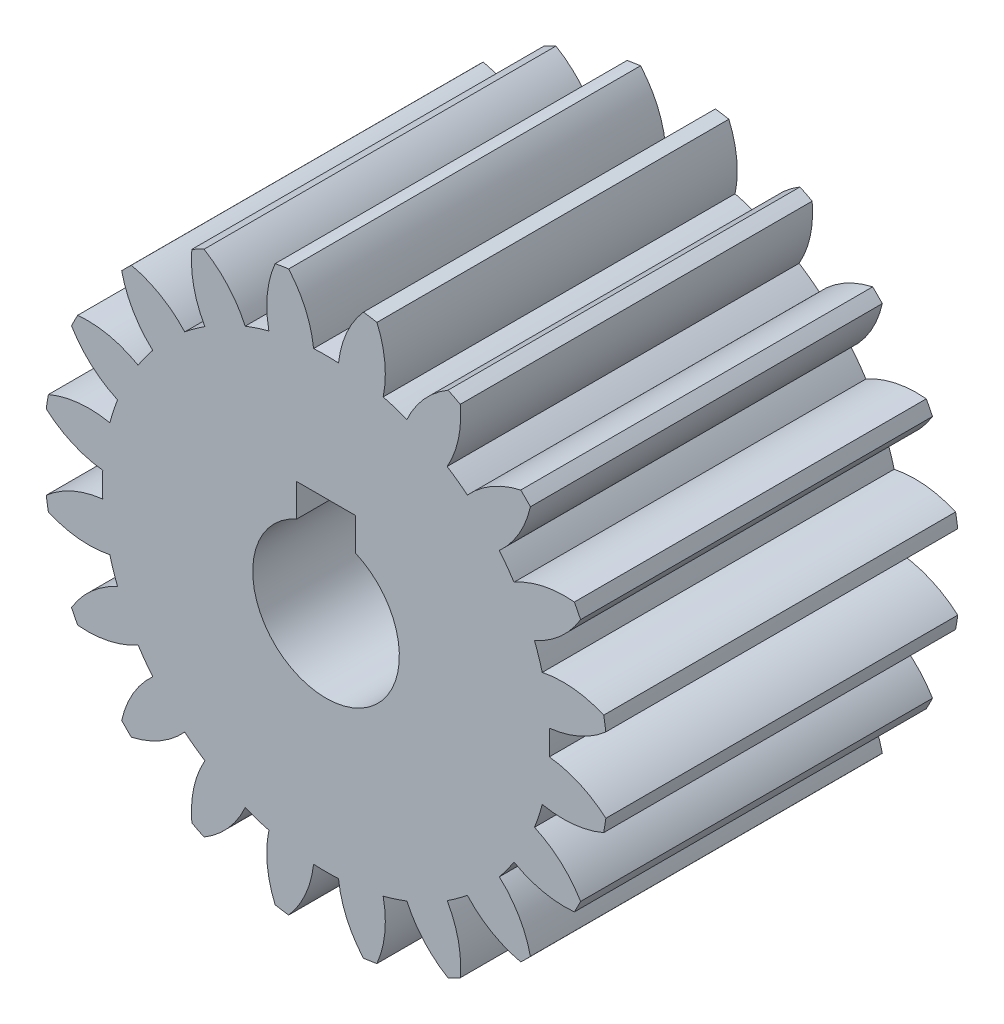
SolidWorks part; units mm, degrees
ref_plane "Front Plane" through (0, 0, 0) normal (0, 0, 1) x (1, 0, 0)
ref_plane "Top Plane" through (0, 0, 0) normal (0, 1, 0) x (1, 0, 0)
ref_plane "Right Plane" through (0, 0, 0) normal (1, 0, 0) x (0, 0, -1)
sketch "Sketch1" plane through (0, 0, 0) normal (0, 0, 1) x (1, 0, 0)
  circle A0 centre (0, 0) radius 19.25
  dimension "D1" = 38.5
extrude "Boss-Extrude1" add sketch "Sketch1" along normal mid plane 24
sketch "Sketch2" plane through (0, 0, 12) normal (0, 0, 1) x (1, 0, 0)
  line L0 (0, 0) -> (0, 17.5) construction
  circle A0 centre (0, 0) radius 17.5 construction
  arc A1 (0.85, 15.2263) -> (-0.85, 15.2263) centre (0, 0) ccw
  arc A2 (0.85, 15.2263) -> (2.55, 19.0804) centre (7.8078, 14.4592) cw
  circle A3 centre (0, 0) radius 19.25 construction
  arc A4 (-0.85, 15.2263) -> (-2.55, 19.0804) centre (-7.8078, 14.4592) ccw
  arc A5 (2.55, 19.0804) -> (-2.55, 19.0804) centre (0, 0) ccw
  point P12 (0, 13.7514)
  dimension "D1" = 35
  dimension "D2" = 30.5
  dimension "D5" = 7
  dimension "D3" = 1.7
  dimension "D4" = 5.1
extrude "Cut-Extrude1" cut sketch "Sketch2" against normal through all
pattern_circular "CirPattern1" count 20 over 360 about axis through (0, 0, 0) along (0, 0, 1) of "Cut-Extrude1"
sketch "Sketch3" plane through (0, 0, 12) normal (0, 0, 1) x (1, 0, 0)
  line L0 (2, 6.8) -> (2, 4.5826)
  line L1 (2, 6.8) -> (-2, 6.8)
  line L2 (-2, 6.8) -> (-2, 4.5826)
  arc A0 (-2, 4.5826) -> (2, 4.5826) centre (0, 0) ccw
  point P5 (0, 6.8)
  dimension "D1" = 10
  dimension "D2" = 4
  dimension "D3" = 11.8
extrude "Cut-Extrude2" cut sketch "Sketch3" against normal through all
